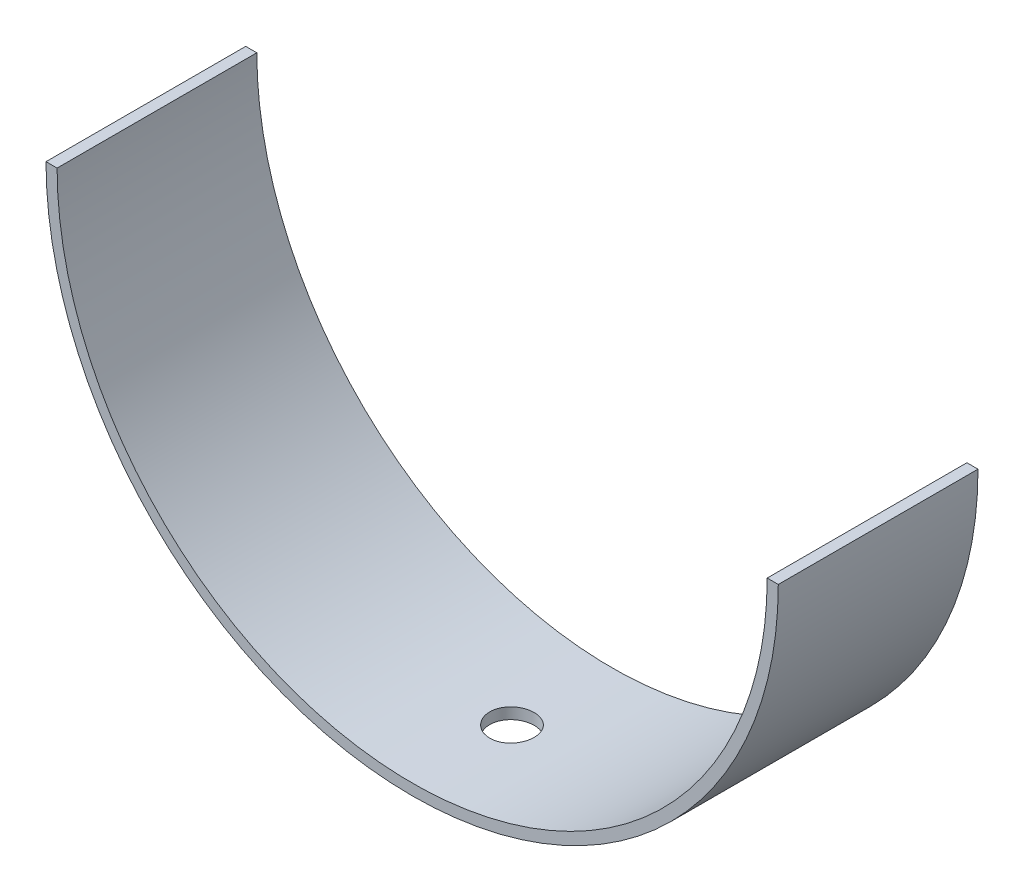
SolidWorks part; units mm, degrees
ref_plane "Alzado" through (0, 0, 0) normal (0, 0, 1) x (1, 0, 0)
ref_plane "Planta" through (0, 0, 0) normal (0, 1, 0) x (1, 0, 0)
ref_plane "Vista lateral" through (0, 0, 0) normal (1, 0, 0) x (0, 0, -1)
sketch "Croquis1" plane through (0, 0, 0) normal (0, 0, 1) x (1, 0, 0)
  line L0 (0, 0) -> (-33, 0) construction
  line L1 (0, 0) -> (33, 0) construction
  line L2 (-32, 0) -> (-33, 0)
  line L3 (33, 0) -> (32, 0)
  arc A0 (-32, 0) -> (32, 0) centre (0, 0) ccw
  arc A1 (-33, 0) -> (33, 0) centre (0, 0) ccw
  dimension "D1" = 66
  dimension "D2" = 64
extrude "Saliente-Extruir1" add sketch "Croquis1" along normal mid plane 18
ref_plane "Plano1" through (0, -33, 0) normal (0, -1, 0) x (1, 0, 0)
sketch "Croquis2" plane through (0, -33, 0) normal (0, -1, 0) x (1, 0, 0)
  circle A0 centre (0, 0) radius 2
  dimension "D1" = 4
extrude "Cortar-Extruir1" cut sketch "Croquis2" against normal blind 10
